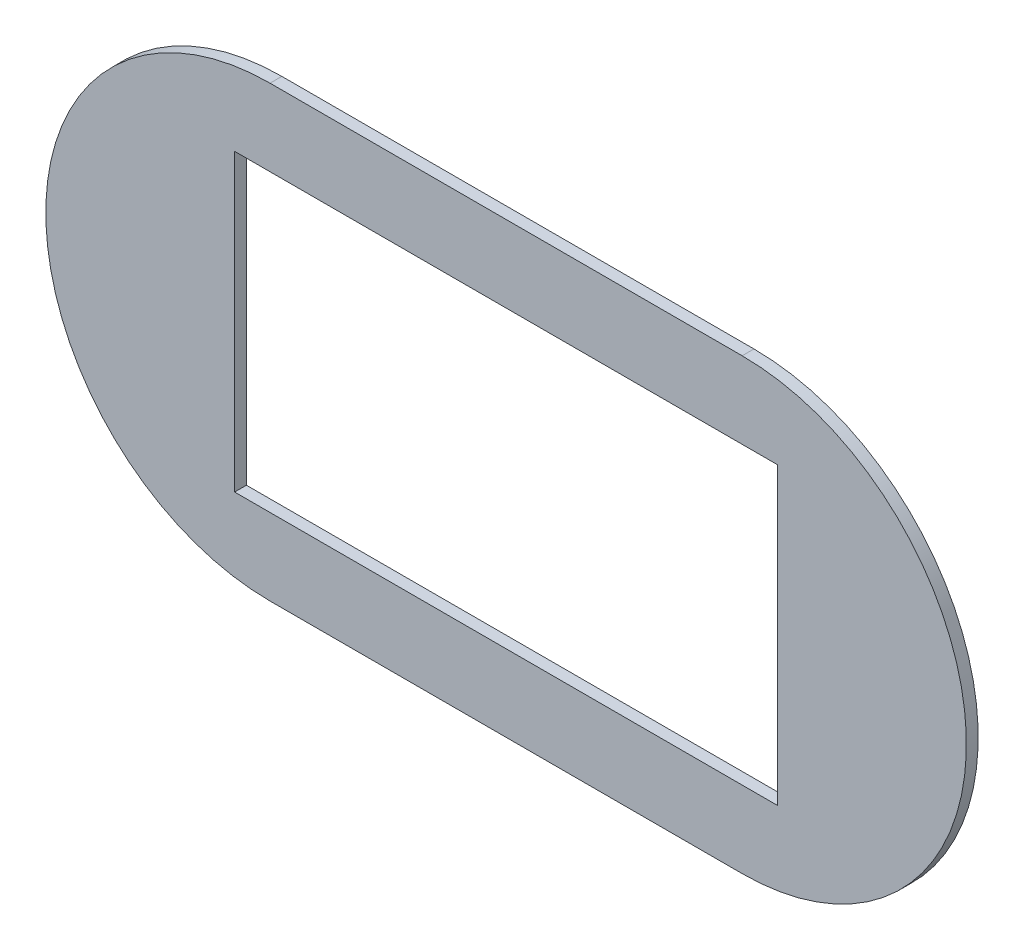
SolidWorks part; units mm, degrees
ref_plane "Спереди" through (0, 0, 0) normal (0, 0, 1) x (1, 0, 0)
ref_plane "Сверху" through (0, 0, 0) normal (0, 1, 0) x (1, 0, 0)
ref_plane "Справа" through (0, 0, 0) normal (1, 0, 0) x (0, 0, -1)
other "Configuration Table"
sketch "Эскиз1" plane through (0, 0, 0) normal (0, 0, 1) x (1, 0, 0)
  line L0 (-40, 0) -> (40, 0) construction
  line L1 (-40, 38) -> (40, 38)
  line L2 (-40, 40) -> (40, 40) construction
  line L3 (-40, -40) -> (40, -40) construction
  line L4 (-40, -38) -> (40, -38)
  arc A0 (-40, 40) -> (-40, -40) centre (-40, 0) ccw construction
  arc A1 (40, -40) -> (40, 40) centre (40, 0) ccw construction
  arc A2 (40, -38) -> (40, 38) centre (40, 0) ccw
  arc A3 (-40, 38) -> (-40, -38) centre (-40, 0) ccw
  point P5 (0, 0)
  dimension "D1" = 80
  dimension "D2" = 160
  dimension "D3" = 2
extrude "Бобышка-Вытянуть1" add sketch "Эскиз1" along normal blind 2
sketch "Эскиз2" plane through (0, 0, 2) normal (0, 0, 1) x (1, 0, 0)
  line L4 (46, -25) -> (-46, -25)
  line L5 (46, -25) -> (46, 25)
  line L6 (46, 25) -> (-46, 25)
  line L7 (-46, -25) -> (-46, 25)
  line L8 (46, -25) -> (-46, 25) construction
  line L9 (46, 25) -> (-46, -25) construction
  point P0 (0, 0)
  point P9 (0, 0)
  dimension "D3" = 50
  dimension "D4" = 92
extrude "Вырез-Вытянуть1" cut sketch "Эскиз2" against normal through all contours L7 L4 L5 L6
